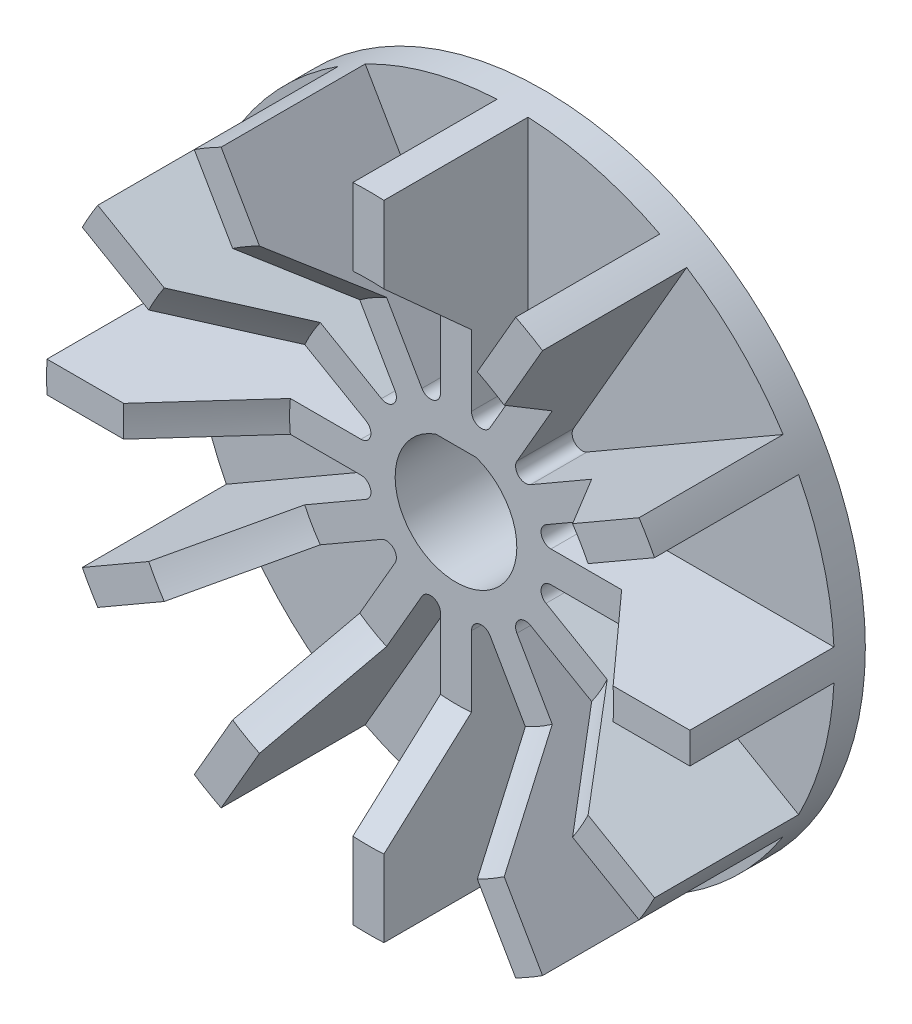
SolidWorks part; units mm, degrees
ref_plane "Front Plane" through (0, 0, 0) normal (0, 0, 1) x (1, 0, 0)
ref_plane "Top Plane" through (0, 0, 0) normal (0, 1, 0) x (1, 0, 0)
ref_plane "Right Plane" through (0, 0, 0) normal (1, 0, 0) x (0, 0, -1)
sketch "Sketch1" plane through (0, 0, 0) normal (0, 0, 1) x (1, 0, 0)
  line L0 (-2.9279, 8.3225) -> (2.9279, 8.3225)
  circle A0 centre (0, 0) radius 8.5725 construction
  arc A1 (-2.9279, 8.3225) -> (2.9279, 8.3225) centre (0, 0) ccw
  circle A2 centre (0, 0) radius 46.6725
  circle A4 centre (0, 0) radius 8.8225 construction
  point P8 (0, 8.8225)
  point P9 (9.0725, 0)
  dimension "D1" = 17.145
  dimension "D3" = 93.345
  dimension "D4" = 0.5
  dimension "D2" = 0.25
extrude "Boss-Extrude1" add sketch "Sketch1" along normal blind 4.5
sketch "Sketch2" plane through (0, 0, 4.5) normal (0, 0, 1) x (1, 0, 0)
  line L0 (-2.25, 46.6182) -> (-2.25, 13.7784)
  line L1 (0, 0) -> (0, 46.6725) construction
  line L2 (2.25, 46.6182) -> (2.25, 13.7784)
  line L3 (21.3606, 41.4976) -> (4.9406, 13.0574)
  line L4 (25.2577, 39.2476) -> (8.8377, 10.8074)
  line L5 (39.2476, 25.2577) -> (10.8074, 8.8377)
  line L6 (41.4976, 21.3606) -> (13.0574, 4.9406)
  line L7 (46.6182, 2.25) -> (13.7784, 2.25)
  line L8 (46.6182, -2.25) -> (13.7784, -2.25)
  line L9 (41.4976, -21.3606) -> (13.0574, -4.9406)
  line L10 (39.2476, -25.2577) -> (10.8074, -8.8377)
  line L11 (25.2577, -39.2476) -> (8.8377, -10.8074)
  line L12 (21.3606, -41.4976) -> (4.9406, -13.0574)
  line L13 (2.25, -46.6182) -> (2.25, -13.7784)
  line L14 (-2.25, -46.6182) -> (-2.25, -13.7784)
  line L15 (-21.3606, -41.4976) -> (-4.9406, -13.0574)
  line L16 (-25.2577, -39.2476) -> (-8.8377, -10.8074)
  line L17 (-39.2476, -25.2577) -> (-10.8074, -8.8377)
  line L18 (-41.4976, -21.3606) -> (-13.0574, -4.9406)
  line L19 (-46.6182, -2.25) -> (-13.7784, -2.25)
  line L20 (-46.6182, 2.25) -> (-13.7784, 2.25)
  line L21 (-41.4976, 21.3606) -> (-13.0574, 4.9406)
  line L22 (-39.2476, 25.2577) -> (-10.8074, 8.8377)
  line L23 (-25.2577, 39.2476) -> (-8.8377, 10.8074)
  line L24 (-21.3606, 41.4976) -> (-4.9406, 13.0574)
  line L25 (-2.25, 13.7784) -> (-4.9406, 13.0574) construction
  line L26 (-3.5953, 13.4179) -> (-12.0797, 45.0822) construction
  line L27 (-3.3187, -12.3856) -> (0, 0) construction
  line L28 (2.9279, 8.3225) -> (-2.9279, 8.3225) construction
  line L29 (2.9279, 8.3225) -> (-2.9279, 8.3225)
  arc A0 (-2.9279, 8.3225) -> (2.9279, 8.3225) centre (0, 0) ccw construction
  arc A1 (-2.9279, 8.3225) -> (2.9279, 8.3225) centre (0, 0) ccw construction
  arc A2 (-2.9279, 8.3225) -> (2.9279, 8.3225) centre (0, 0) ccw
  arc A4 (2.25, 46.6182) -> (-2.25, 46.6182) centre (0, 0) ccw
  circle A5 centre (0, 0) radius 46.6725 construction
  arc A6 (25.2577, 39.2476) -> (21.3606, 41.4976) centre (0, 0) ccw
  arc A7 (41.4976, 21.3606) -> (39.2476, 25.2577) centre (0, 0) ccw
  arc A8 (46.6182, -2.25) -> (46.6182, 2.25) centre (0, 0) ccw
  arc A9 (39.2476, -25.2577) -> (41.4976, -21.3606) centre (0, 0) ccw
  arc A10 (21.3606, -41.4976) -> (25.2577, -39.2476) centre (0, 0) ccw
  arc A11 (-2.25, -46.6182) -> (2.25, -46.6182) centre (0, 0) ccw
  arc A12 (-25.2577, -39.2476) -> (-21.3606, -41.4976) centre (0, 0) ccw
  arc A13 (-41.4976, -21.3606) -> (-39.2476, -25.2577) centre (0, 0) ccw
  arc A14 (-46.6182, 2.25) -> (-46.6182, -2.25) centre (0, 0) ccw
  arc A15 (-39.2476, 25.2577) -> (-41.4976, 21.3606) centre (0, 0) ccw
  arc A16 (-21.3606, 41.4976) -> (-25.2577, 39.2476) centre (0, 0) ccw
  arc A17 (-2.25, 13.7784) -> (-4.9406, 13.0574) centre (-3.6919, 13.7784) cw
  arc A18 (4.9406, 13.0574) -> (2.25, 13.7784) centre (3.6919, 13.7784) cw
  arc A19 (10.8074, 8.8377) -> (8.8377, 10.8074) centre (10.0865, 10.0865) cw
  arc A20 (13.7784, 2.25) -> (13.0574, 4.9406) centre (13.7784, 3.6919) cw
  arc A21 (13.0574, -4.9406) -> (13.7784, -2.25) centre (13.7784, -3.6919) cw
  arc A22 (8.8377, -10.8074) -> (10.8074, -8.8377) centre (10.0865, -10.0865) cw
  arc A23 (2.25, -13.7784) -> (4.9406, -13.0574) centre (3.6919, -13.7784) cw
  arc A24 (-4.9406, -13.0574) -> (-2.25, -13.7784) centre (-3.6919, -13.7784) cw
  arc A25 (-10.8074, -8.8377) -> (-8.8377, -10.8074) centre (-10.0865, -10.0865) cw
  arc A26 (-13.7784, -2.25) -> (-13.0574, -4.9406) centre (-13.7784, -3.6919) cw
  arc A27 (-13.0574, 4.9406) -> (-13.7784, 2.25) centre (-13.7784, 3.6919) cw
  arc A28 (-8.8377, 10.8074) -> (-10.8074, 8.8377) centre (-10.0865, 10.0865) cw
  point P60 (-3.3187, -12.3856)
  point P62 (-2.2834, -8.5219)
  point P64 (4.9406, 13.4179)
  circle M51 centre (0, 0) radius 46.6725
  arc M53 (2.9279, 8.3225) -> (-2.9279, 8.3225) centre (0, 0) cw
  dimension "D1" = 4.5
  dimension "D4" = 4
  dimension "D2" = 12
  dimension "D3" = 12
extrude "Boss-Extrude2" add sketch "Sketch2" along normal blind 25.4 from surface at -4.5 contours L23 A28 L22 L21 A27 L20 L19 A26 L18 L17 A25 L16 L15 A24 L14 L13 A23 L12 L11 A22 L10 L9 A21 L8 L7 A20 L6 L5 A19 L4 L3 A18 L2 L0 A17 L24 A2 M51 M53 starting at face at (46.6725, 0, 0)
sketch "Sketch3" plane through (0, 0, 0) normal (0, 1, 0) x (1, 0, 0)
  line L0 (0, 0) -> (0, -25.4) construction
  line L1 (-8.8225, -25.4) -> (8.8225, -25.4) construction
  line L2 (-24.13, -25.4) -> (24.13, -25.4) construction
  line L3 (46.6182, -25.4) -> (13.7784, -25.4) construction
  line L4 (-24.13, -12.7) -> (-6.35, -12.7)
  line L5 (-24.13, -12.7) -> (-35.56, -25.4)
  line L6 (-46.6182, -25.4) -> (-13.7784, -25.4) construction
  line L7 (-35.56, -25.4) -> (-6.35, -25.4)
  line L9 (-24.13, -12.7) -> (24.13, -12.7) construction
  line L11 (-6.35, -12.7) -> (-6.35, -25.4)
  point P9 (0, -25.4)
  dimension "D1" = 48.26
  dimension "D3" = 11.43
  dimension "D4" = 12.7
  dimension "D2" = 12.7
revolve "Cut-Revolve1" cut sketch "Sketch3" angle 360 about L0
